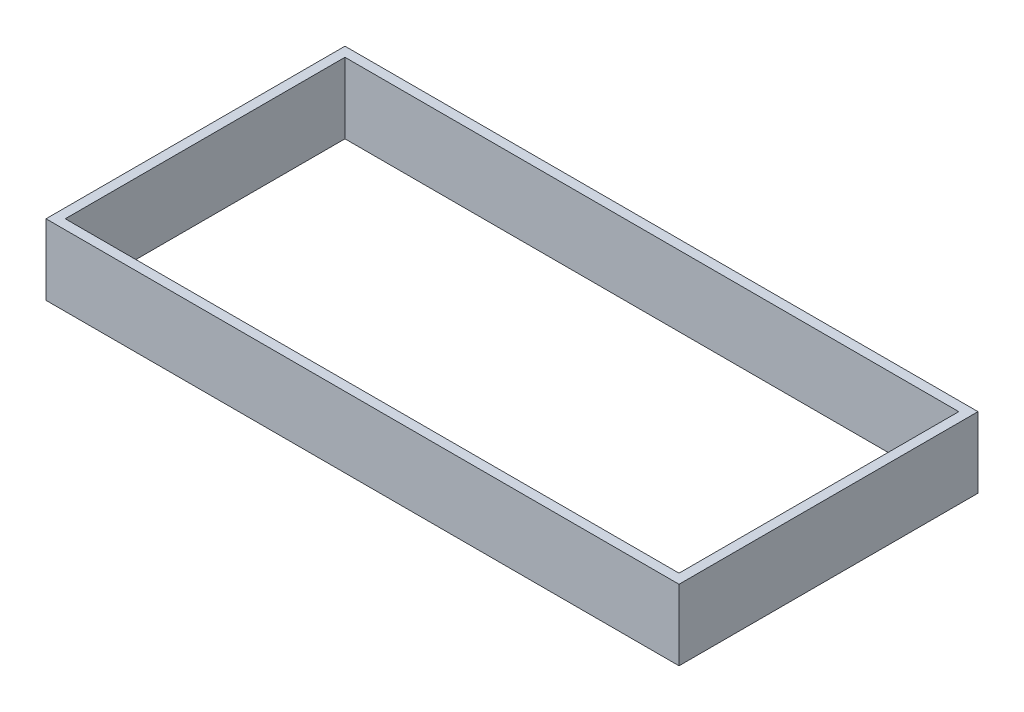
SolidWorks part; units mm, degrees
ref_plane "Front Plane" through (0, 0, 0) normal (0, 0, 1) x (1, 0, 0)
ref_plane "Top Plane" through (0, 0, 0) normal (0, 1, 0) x (1, 0, 0)
ref_plane "Right Plane" through (0, 0, 0) normal (1, 0, 0) x (0, 0, -1)
sketch "Sketch1" plane through (0, 0, 0) normal (0, 1, 0) x (1, 0, 0)
  line L0 (0, 31.1) -> (0, -31.1) construction
  line L1 (-65.85, 31.1) -> (65.85, 31.1)
  line L2 (-65.85, 31.1) -> (-65.85, -31.1)
  line L3 (-65.85, -31.1) -> (65.85, -31.1)
  line L4 (65.85, 31.1) -> (65.85, -31.1)
  line L5 (-63.85, 29.1) -> (63.85, 29.1)
  line L6 (-63.85, 29.1) -> (-63.85, -29.1)
  line L7 (-63.85, -29.1) -> (63.85, -29.1)
  line L8 (63.85, 29.1) -> (63.85, -29.1)
  point P10 (0, 0)
  point P11 (0, 0)
  point P13 (0, 0)
  dimension "D1" = 131.7
  dimension "D2" = 62.2
  dimension "D3" = 2
  dimension "D4" = 2
  dimension "D5" = 2
  dimension "D6" = 2
extrude "Boss-Extrude1" add sketch "Sketch1" along normal blind 14.7 contours L1 L4 L3 L2 | L7 L8 L5 L6
equation "\"D4@Sketch1\"=\"D3@Sketch1\""
equation "\"D5@Sketch1\"=\"D3@Sketch1\""
equation "\"D6@Sketch1\"=\"D5@Sketch1\""
